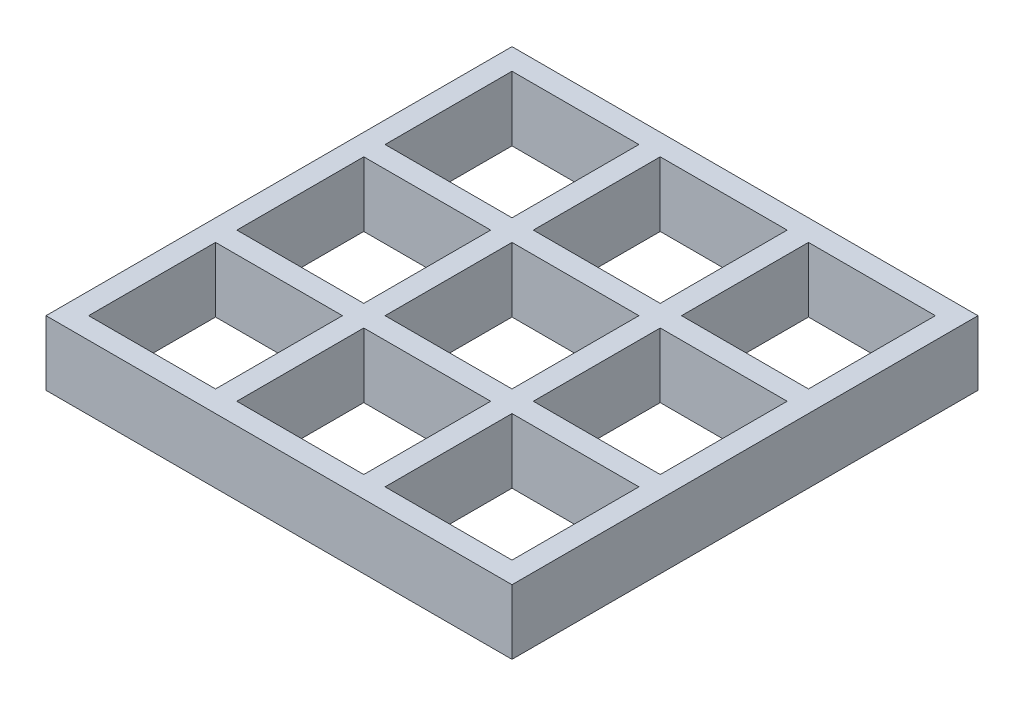
SolidWorks part; units mm, degrees
ref_plane "Front Plane" through (0, 0, 0) normal (0, 0, 1) x (1, 0, 0)
ref_plane "Top Plane" through (0, 0, 0) normal (0, 1, 0) x (1, 0, 0)
ref_plane "Right Plane" through (0, 0, 0) normal (1, 0, 0) x (0, 0, -1)
sketch "Sketch1" plane through (0, 0, 0) normal (0, 1, 0) x (1, 0, 0)
  line L0 (3.54, 2.65) -> (8.84, 2.65)
  line L1 (-2.65, -2.65) -> (2.65, -2.65)
  line L2 (-2.65, -2.65) -> (-2.65, 2.65)
  line L3 (-2.65, 2.65) -> (2.65, 2.65)
  line L4 (2.65, -2.65) -> (2.65, 2.65)
  line L5 (-2.65, -2.65) -> (2.65, 2.65) construction
  line L6 (-2.65, 2.65) -> (2.65, -2.65) construction
  line L7 (3.54, -2.65) -> (3.54, 2.65)
  line L8 (3.54, -2.65) -> (8.84, -2.65)
  line L9 (8.84, -2.65) -> (8.84, 2.65)
  line L10 (9.73, 2.65) -> (15.03, 2.65)
  line L11 (9.73, -2.65) -> (9.73, 2.65)
  line L12 (9.73, -2.65) -> (15.03, -2.65)
  line L13 (15.03, -2.65) -> (15.03, 2.65)
  line L14 (3.54, 8.84) -> (8.84, 8.84)
  line L15 (3.54, 3.54) -> (3.54, 8.84)
  line L16 (3.54, 3.54) -> (8.84, 3.54)
  line L17 (8.84, 3.54) -> (8.84, 8.84)
  line L18 (9.73, 8.84) -> (15.03, 8.84)
  line L19 (9.73, 3.54) -> (9.73, 8.84)
  line L20 (9.73, 3.54) -> (15.03, 3.54)
  line L21 (15.03, 3.54) -> (15.03, 8.84)
  line L22 (3.54, 15.03) -> (8.84, 15.03)
  line L23 (3.54, 9.73) -> (3.54, 15.03)
  line L24 (3.54, 9.73) -> (8.84, 9.73)
  line L25 (8.84, 9.73) -> (8.84, 15.03)
  line L26 (9.73, 15.03) -> (15.03, 15.03)
  line L27 (9.73, 9.73) -> (9.73, 15.03)
  line L28 (9.73, 9.73) -> (15.03, 9.73)
  line L29 (15.03, 9.73) -> (15.03, 15.03)
  line L30 (-2.65, 8.84) -> (2.65, 8.84)
  line L31 (-2.65, 3.54) -> (-2.65, 8.84)
  line L32 (-2.65, 3.54) -> (2.65, 3.54)
  line L33 (2.65, 3.54) -> (2.65, 8.84)
  line L34 (-2.65, 15.03) -> (2.65, 15.03)
  line L35 (-2.65, 9.73) -> (-2.65, 15.03)
  line L36 (-2.65, 9.73) -> (2.65, 9.73)
  line L37 (2.65, 9.73) -> (2.65, 15.03)
  line L38 (-3.54, -3.54) -> (15.92, -3.54)
  line L39 (-3.54, -3.54) -> (-3.54, 15.92)
  line L40 (-3.54, 15.92) -> (15.92, 15.92)
  line L41 (15.92, -3.54) -> (15.92, 15.92)
  point P0 (0, 0)
  point P8 (16.1113, 15.92)
  dimension "D1" = 5.3
  dimension "D4" = 0.89
  dimension "D5" = 0.89
  dimension "D6" = 6.19
  dimension "D7" = 0.89
  dimension "D8" = 6.19
  dimension "D9" = 0.89
  dimension "D2" = 3
  dimension "D3" = 3
extrude "Boss-Extrude1" add sketch "Sketch1" along normal blind 2.7
